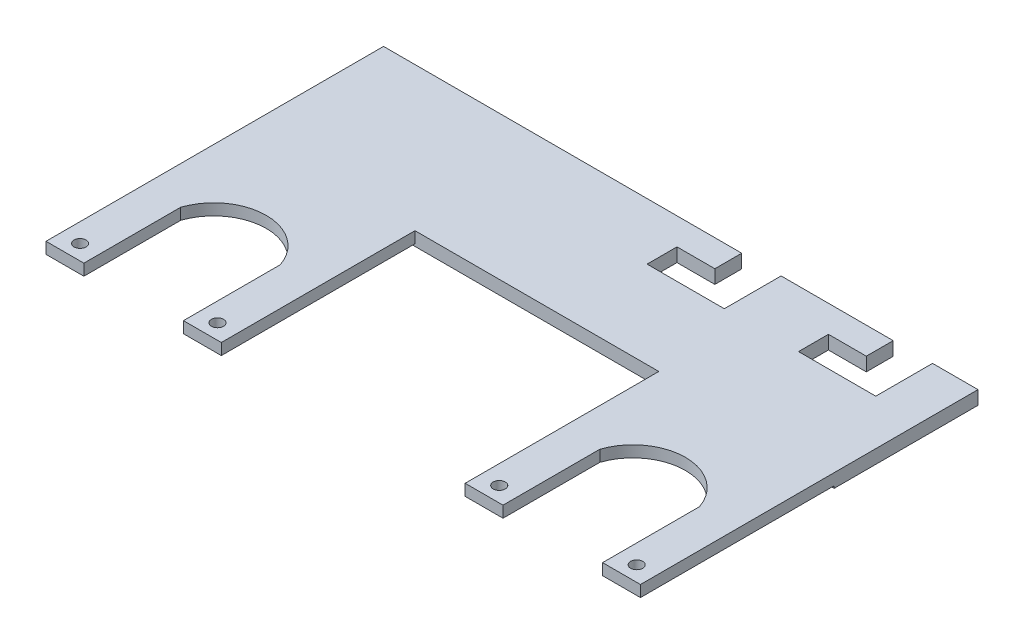
SolidWorks part; units mm, degrees
material "ABS"
ref_plane "前视基准面" through (0, 0, 0) normal (0, 0, 1) x (1, 0, 0)
ref_plane "上视基准面" through (0, 0, 0) normal (0, 1, 0) x (1, 0, 0)
ref_plane "右视基准面" through (0, 0, 0) normal (1, 0, 0) x (0, 0, -1)
other "Configuration Table"
sketch "草图1" plane through (0, 0, 0) normal (1, 0, 0) x (0, 0, -1)
  line L0 (-19, -1.8) -> (19, -1.8)
  line L1 (-19, -1.8) -> (19, -1.8) construction
  line L2 (-19, -1.8) -> (-19, 1.8)
  line L3 (-19, 1.8) -> (19, 1.8)
  line L4 (19, -1.8) -> (19, 1.8)
  line L5 (-19, -1.8) -> (19, 1.8) construction
  line L6 (-19, 1.8) -> (19, -1.8) construction
  line L12 (3, 1.8) -> (3, -1.8) construction
  point P0 (0, 0)
  dimension "D1" = 38
  dimension "D2" = 3.6
  dimension "D3" = 22
extrude "凸台-拉伸1" add sketch "草图1" along normal blind 157
sketch "草图2" plane through (0, 1.8, 0) normal (0, 1, 0) x (1, 0, 0)
  line L0 (0, -19) -> (0, 19) construction
  line L1 (78.5, 31.9444) -> (78.5, -56.65) construction
  line L2 (157, -19) -> (0, -19) construction
  line L3 (10, -19) -> (36.3, -19)
  line L4 (10, -19) -> (10, -70.15) construction
  line L5 (10, -70.15) -> (36.3, -70.15) construction
  line L6 (36.3, -19) -> (36.3, -70.15) construction
  line L7 (10, -70.15) -> (10, -44.575) construction
  line L8 (36.3, -70.15) -> (36.3, -44.575) construction
  line L9 (10, -70.15) -> (0, -70.15)
  line L10 (0, -70.15) -> (0, -19)
  line L11 (36.3, -70.15) -> (46.3, -70.15)
  line L12 (46.3, -70.15) -> (46.3, -19)
  line L13 (46.3, -19) -> (0, -19)
  line L14 (9.0098, -62.15) -> (42.2827, -62.15) construction
  line L22 (0, -29) -> (46.3, -29) construction
  line L23 (10, -70.15) -> (10, -49)
  line L24 (36.3, -70.15) -> (36.3, -49)
  line L25 (10, -49) -> (10, -44.575)
  line L26 (157, -29) -> (110.7, -29) construction
  line L27 (147.9902, -62.15) -> (114.7173, -62.15) construction
  line L28 (120.7, -70.15) -> (120.7, -44.575) construction
  line L29 (147, -70.15) -> (147, -44.575) construction
  line L30 (120.7, -19) -> (120.7, -70.15) construction
  line L31 (147, -70.15) -> (120.7, -70.15) construction
  line L32 (147, -19) -> (147, -70.15) construction
  line L40 (120.7, -44.575) -> (120.7, -49)
  line L41 (36.3, -44.575) -> (36.3, -49)
  line L42 (147, -49) -> (147, -44.575)
  line L43 (120.7, -70.15) -> (120.7, -49)
  line L44 (147, -70.15) -> (147, -49)
  line L45 (110.7, -19) -> (157, -19)
  line L46 (110.7, -70.15) -> (110.7, -19)
  line L47 (120.7, -70.15) -> (110.7, -70.15)
  line L48 (157, -70.15) -> (157, -19)
  line L49 (147, -70.15) -> (157, -70.15)
  line L50 (147, -19) -> (120.7, -19)
  circle A0 centre (23.15, -49) radius 13.15 construction
  arc A1 (36.3, -44.575) -> (10, -44.575) centre (23.15, -49) ccw construction
  circle A3 centre (5, -66.15) radius 1.6
  circle A4 centre (41.3, -66.15) radius 1.6
  arc A7 (36.3, -49) -> (10, -49) centre (23.15, -49) ccw construction
  arc A8 (120.7, -49) -> (147, -49) centre (133.85, -49) cw construction
  arc A13 (10, -44.575) -> (36.3, -44.575) centre (23.15, -49) cw
  arc A14 (120.7, -44.575) -> (147, -44.575) centre (133.85, -49) cw construction
  circle A15 centre (133.85, -49) radius 13.15 construction
  arc A16 (147, -44.575) -> (120.7, -44.575) centre (133.85, -49) ccw
  circle A17 centre (115.7, -66.15) radius 1.6
  circle A18 centre (152, -66.15) radius 1.6
  dimension "D2" = 26.3
  dimension "D10" = 3.2
  dimension "D12" = 3.2
  dimension "D13" = 5
  dimension "D4" = 10
  dimension "D5" = 8
  dimension "D6" = 10
  dimension "D7" = 10
  dimension "D8" = 4
  dimension "D9" = 4
  dimension "D11" = 5
  dimension "D14" = 20
  dimension "D27" = 78.5
extrude "凸台-拉伸2" add sketch "草图2" against normal blind 3
sketch "草图3" plane through (0, 1.8, 0) normal (0, 1, 0) x (1, 0, 0)
  circle A0 centre (23.15, -49) radius 51.7 construction
  circle A1 centre (133.85, -49) radius 51.7 construction
  dimension "D1" = 103.4
sketch "草图4" plane through (0, 1.8, 0) normal (0, 1, 0) x (1, 0, 0)
  line L8 (124.8, 11.7) -> (124.8, 4.2)
  line L9 (124.8, 4.2) -> (134.8, 4.2)
  line L10 (134.8, 4.2) -> (134.8, 11.7)
  line L11 (134.8, 11.7) -> (124.8, 11.7)
  line L12 (124.8, 11.7) -> (124.8, 4.2) construction
  line L13 (124.8, 4.2) -> (134.8, 4.2) construction
  line L14 (134.8, 4.2) -> (134.8, 11.7) construction
  line L15 (134.8, 11.7) -> (124.8, 11.7) construction
  line L17 (94.8, 4.2) -> (104.8, 4.2) construction
  line L18 (94.8, 4.2) -> (94.8, 19) construction
  line L19 (94.8, 19) -> (104.8, 19) construction
  line L20 (94.8, 4.2) -> (94.8, 11.7)
  line L21 (94.8, 11.7) -> (84.8, 11.7)
  line L22 (84.8, 11.7) -> (84.8, 4.2)
  line L23 (84.8, 4.2) -> (94.8, 4.2)
  line L24 (94.8, 4.2) -> (94.8, 11.7) construction
  line L25 (94.8, 11.7) -> (84.8, 11.7) construction
  line L26 (84.8, 11.7) -> (84.8, 4.2) construction
  line L27 (84.8, 4.2) -> (94.8, 4.2) construction
  line L28 (104.8, 4.2) -> (104.8, 19) construction
  line L29 (134.8, 4.2) -> (144.8, 4.2) construction
  line L30 (134.8, 4.2) -> (134.8, 19) construction
  line L31 (134.8, 19) -> (144.8, 19) construction
  line L32 (144.8, 4.2) -> (144.8, 19) construction
  line L33 (157, 19) -> (0, 19) construction
  line L35 (94.8, 19) -> (94.8, 11.7) construction
  line L36 (94.8, 11.7) -> (84.8, 11.7) construction
  line L37 (84.8, 11.7) -> (84.8, 4.2) construction
  line L38 (84.8, 4.2) -> (104.8, 4.2) construction
  line L39 (104.8, 4.2) -> (104.8, 19) construction
  line L40 (104.8, 19) -> (94.8, 19) construction
  line L41 (134.8, 19) -> (134.8, 11.7) construction
  line L42 (134.8, 11.7) -> (124.8, 11.7) construction
  line L43 (124.8, 11.7) -> (124.8, 4.2) construction
  line L44 (124.8, 4.2) -> (144.8, 4.2) construction
  line L45 (144.8, 4.2) -> (144.8, 19) construction
  line L46 (144.8, 19) -> (134.8, 19) construction
  line L47 (105, 19.2) -> (94.6, 19.2)
  line L48 (94.6, 19.2) -> (94.6, 11.9)
  line L49 (94.6, 11.9) -> (84.6, 11.9)
  line L50 (84.6, 11.9) -> (84.6, 4)
  line L51 (84.6, 4) -> (105, 4)
  line L52 (105, 4) -> (105, 19.2)
  line L53 (145, 19.2) -> (134.6, 19.2)
  line L54 (134.6, 19.2) -> (134.6, 11.9)
  line L55 (134.6, 11.9) -> (124.6, 11.9)
  line L56 (124.6, 11.9) -> (124.6, 4)
  line L57 (124.6, 4) -> (145, 4)
  line L58 (145, 4) -> (145, 19.2)
  dimension "D3" = 10
  dimension "D4" = 10
  dimension "D1" = 3
  dimension "D2" = 3
  dimension "D5" = 0.2
extrude "切除-拉伸1" cut sketch "草图4" against normal through all
